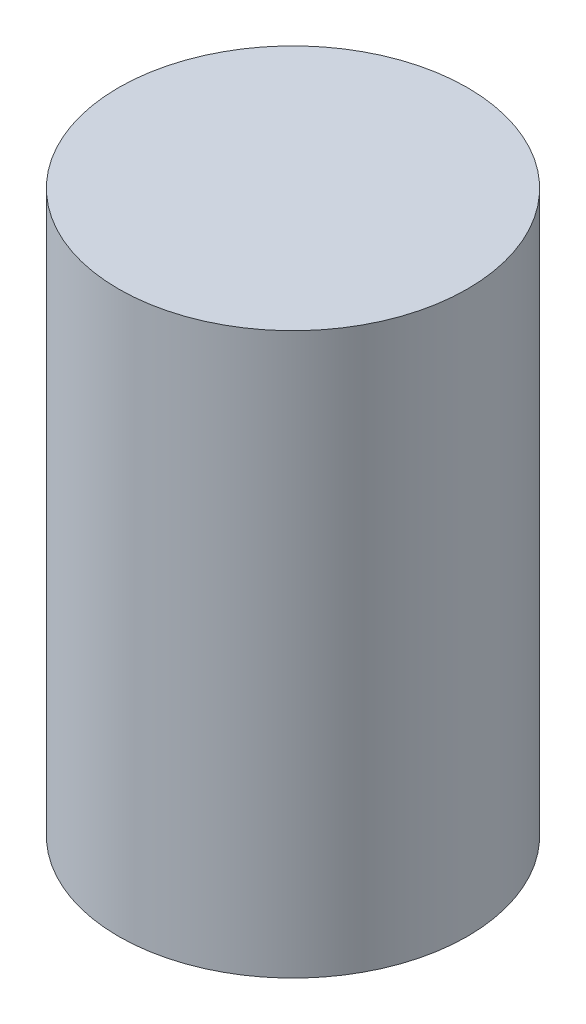
SolidWorks part; units mm, degrees
other "Stage 3"
ref_plane "Front Plane" through (0, 0, 0) normal (0, 0, 1) x (1, 0, 0)
ref_plane "Top Plane" through (0, 0, 0) normal (0, 1, 0) x (1, 0, 0)
ref_plane "Right Plane" through (0, 0, 0) normal (1, 0, 0) x (0, 0, -1)
sketch "Sketch1" plane through (0, 0, 0) normal (0, 0, 1) x (1, 0, 0)
  line L0 (-607.797, 0) -> (607.797, 0) construction
  line L1 (0, 0) -> (0, 989.6578) construction
  line L3 (0, 0) -> (112, 0)
  line L4 (0, 0) -> (0, -360)
  line L5 (0, -360) -> (112, -360)
  line L6 (112, 0) -> (112, -360)
  point P4 (0, 0)
  dimension "D1" = 360
  dimension "D2" = 112
revolve "Revolve1" add sketch "Sketch1" angle 360 about L1
